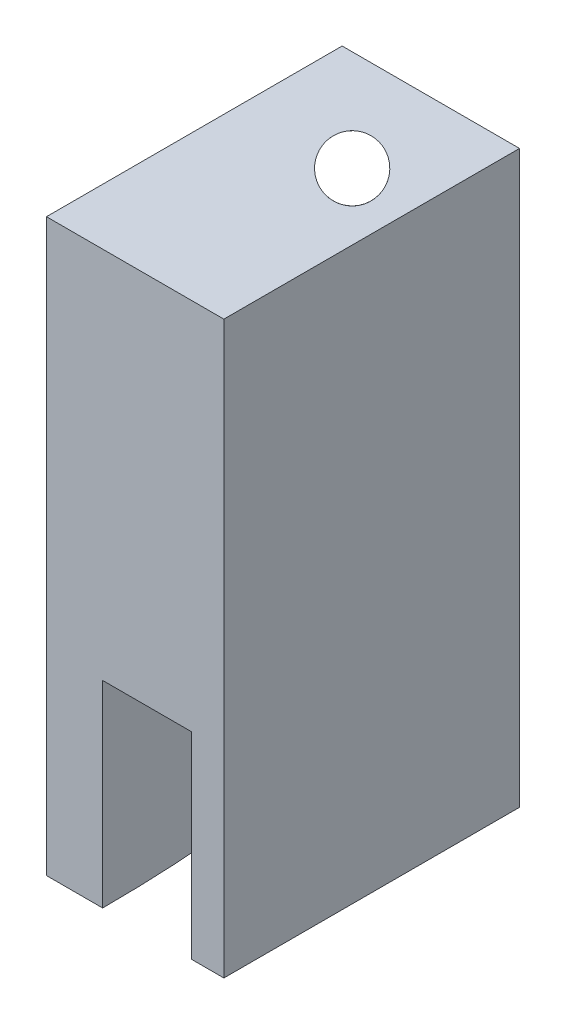
SolidWorks part; units mm, degrees
ref_plane "Front Plane" through (0, 0, 0) normal (0, 0, 1) x (1, 0, 0)
ref_plane "Top Plane" through (0, 0, 0) normal (0, 1, 0) x (1, 0, 0)
ref_plane "Right Plane" through (0, 0, 0) normal (1, 0, 0) x (0, 0, -1)
sketch "Sketch1" plane through (0, 0, 0) normal (0, 1, 0) x (1, 0, 0)
  line L0 (108.5, 0) -> (123.5, 0) construction
  line L1 (123.5, 0) -> (123.5, 25) construction
  line L3 (123.5, 25) -> (108.5, 25)
  line L4 (123.5, 25) -> (123.5, 0)
  line L5 (123.5, 0) -> (108.5, 0)
  line L6 (108.5, 25) -> (108.5, 0)
  dimension "D3" = 15
  dimension "D5" = 25
extrude "Boss-Extrude1" add sketch "Sketch1" along normal blind 42
sketch "Sketch2" plane through (0, 0, 0) normal (0, 1, 0) x (1, 0, 0)
  line L0 (110.4562, 25) -> (118.1337, 25)
  line L1 (123.5, 25) -> (108.5, 25) construction
  line L2 (113.25, 0) -> (120.75, 0)
  arc A0 (120.75, 0) -> (118.1337, 25) centre (0, 0) ccw
  arc A1 (113.25, 0) -> (110.4562, 25) centre (0, 0) ccw
  dimension "D1" = 226.5
  dimension "D2" = 241.5
extrude "Cut-Extrude1" cut sketch "Sketch2" along normal blind 16.6667
sketch "Sketch3" plane through (0, 42, 0) normal (0, 1, 0) x (1, 0, 0)
  line L1 (108.5, 0) -> (123.5, 0)
  line L2 (108.5, 0) -> (108.5, 25)
  line L3 (108.5, 25) -> (123.5, 25)
  line L4 (123.5, 0) -> (123.5, 25)
extrude "Boss-Extrude2" add sketch "Sketch3" along normal blind 6.25
ref_plane "Plane1" through (0, 0, 0) normal (0.5774, 0.5773, 0.5774) x (0.7071, 0, -0.7071)
sketch "Sketch5" plane through (0, 0, 0) normal (0.5774, 0.5773, 0.5774) x (0.7071, 0, -0.7071)
  line L0 (0, 0) -> (0, -43.215) construction
  circle A0 centre (95, -2) radius 2.25
  dimension "D1" = 4.5
  dimension "D2" = 2
  dimension "D3" = 95
extrude "Cut-Extrude2" cut sketch "Sketch5" along normal up to surface (93.3827 mm away)
